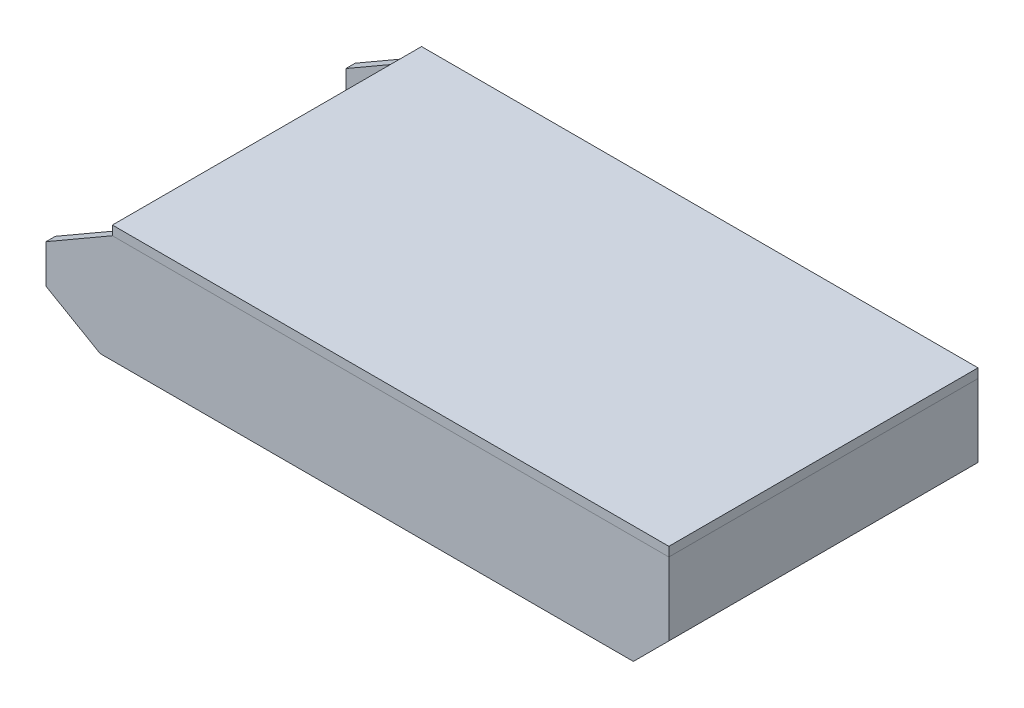
SolidWorks part; units mm, degrees
ref_plane "Front Plane" through (0, 0, 0) normal (0, 0, 1) x (1, 0, 0)
ref_plane "Top Plane" through (0, 0, 0) normal (0, 1, 0) x (1, 0, 0)
ref_plane "Right Plane" through (0, 0, 0) normal (1, 0, 0) x (0, 0, -1)
sketch "Sketch1" plane through (0, 0, 0) normal (0, 1, 0) x (1, 0, 0)
  line L0 (-180, 0) -> (180, 0) construction
  line L1 (-180, -100) -> (-180, 100) construction
  line L2 (-180, 100) -> (180, 100) construction
  line L3 (180, 100) -> (180, -100) construction
  line L4 (180, -100) -> (-180, -100) construction
  point P4 (0, 0)
  point P7 (-180, 0)
ref_plane "Back" through (180, 0, 0) normal (1, 0, 0) x (0, 0, -1)
ref_plane "Front" through (-180, 0, 0) normal (-1, 0, 0) x (0, 0, 1)
ref_plane "Left" through (0, 0, 100) normal (0, 0, 1) x (1, 0, 0)
ref_plane "Right" through (0, 0, -100) normal (0, 0, -1) x (-1, 0, 0)
sketch3d "3DSketch1"
  line L0 (-180, 0, 100) -> (-180, 300.6938, 100) construction
  line L1 (-180, 0, -100) -> (-180, 287.9975, -100) construction
  line L2 (180, 0, -100) -> (180, 282.9498, -100) construction
  line L3 (180, 0, 100) -> (180, 391.3038, 100) construction
  line L4 (-110, 0, -100) -> (-110, 0, 100) construction
  line L5 (-180, 0, -100) -> (180, 0, -100) construction
  line L6 (180, 0, 100) -> (-180, 0, 100) construction
  line L7 (157.0424, 0, 100) -> (157.0424, 0, -100) construction
  dimension "D1" = 110
  dimension "D2" = 157.0424
ref_plane "FrontMainBody" through (-55, -55, 0) normal (-0.7071, -0.7071, 0) x (0, 0, 1)
sketch "Left Panel(Main)" plane through (0, 0, 100) normal (0, 0, 1) x (1, 0, 0)
  line L0 (157.0424, 0) -> (-187.9576, 0)
  line L2 (-180, -200000) -> (-180, 200300.6938) construction
  line L3 (-180, 70) -> (180, 70)
  line L4 (180, -200000) -> (180, 200391.3038) construction
  line L5 (180, 70) -> (180, 22.9576)
  line L6 (180, 22.9576) -> (157.0424, 0)
  line L7 (-180, 70) -> (-222.9576, 45.1984)
  line L8 (-222.9576, 45.1984) -> (-222.9576, 20.2073)
  line L9 (-222.9576, 20.2073) -> (-187.9576, 0)
  line L10 (-180, 70) -> (-110, 0) construction
  dimension "D2" = 150
  dimension "D3" = 150
  dimension "D4" = 45
  dimension "D5" = 135
  dimension "D6" = 345
  dimension "D7" = 70
  dimension "D1" = 35
  dimension "D8" = 157.0424
sketch "Right Panel" plane through (0, 0, -100) normal (0, 0, -1) x (-1, 0, 0)
  line L0 (-180, 70) -> (180, 70)
  line L1 (180, 70) -> (222.9576, 45.1984)
  line L2 (222.9576, 45.1984) -> (222.9576, 20.2073)
  line L3 (222.9576, 20.2073) -> (187.9576, 0)
  line L4 (187.9576, 0) -> (-157.0424, 0)
  line L5 (-157.0424, 0) -> (-180, 22.9576)
  line L6 (-180, 22.9576) -> (-180, 70)
sketch3d "3DSketch4"
  line L0 (157.0424, 0, 100) -> (180, 22.9576, 100)
  line L1 (180, 22.9576, 100) -> (180, 70, 100)
  line L2 (180, 70, 100) -> (-180, 70, 100)
  line L3 (-180, 70, 100) -> (-222.9576, 45.1984, 100)
  line L4 (-222.9576, 45.1984, 100) -> (-222.9576, 20.2073, 100)
  line L5 (-222.9576, 20.2073, 100) -> (-187.9576, 0, 100)
  line L6 (-187.9576, 0, 100) -> (157.0424, 0, 100)
  line L7 (-187.9576, 0, -100) -> (157.0424, 0, -100)
  line L8 (-222.9576, 20.2073, -100) -> (-187.9576, 0, -100)
  line L9 (-222.9576, 45.1984, -100) -> (-222.9576, 20.2073, -100)
  line L10 (-180, 70, -100) -> (-222.9576, 45.1984, -100)
  line L11 (180, 70, -100) -> (-180, 70, -100)
  line L12 (180, 22.9576, -100) -> (180, 70, -100)
  line L13 (157.0424, 0, -100) -> (180, 22.9576, -100)
sketch "Sketch7" plane through (180, 0, 0) normal (1, 0, 0) x (0, 0, -1)
  line L0 (-94, 22.9576) -> (94, 22.9576)
  line L1 (-94, 22.9576) -> (-94, 70)
  line L2 (-94, 70) -> (94, 70)
  line L3 (94, 22.9576) -> (94, 70)
  dimension "D1" = 188
  dimension "D2" = 6
ref_plane "Plane2" through (78.5212, -78.5212, 0) normal (-0.7071, 0.7071, 0) x (0, 0, 1)
sketch "Sketch8" plane through (78.5212, -78.5212, 0) normal (-0.7071, 0.7071, 0) x (0, 0, 1)
  line L0 (-94, 143.5127) -> (-94, 111.0457)
  line L1 (-94, 111.0457) -> (94, 111.0457)
  line L2 (94, 111.0457) -> (94, 143.5127)
  line L3 (-94, 143.5127) -> (94, 143.5127)
  line L8 (100, 111.0457) -> (-100, 111.0457) construction
sketch "Sketch9" plane through (0, 0, 0) normal (0, 1, 0) x (1, 0, 0)
  line L0 (-110, -94) -> (151.0424, -94)
  line L1 (-110, 100) -> (-110, -100) construction
  line L3 (151.0424, -94) -> (151.0424, 94)
  line L4 (151.0424, 94) -> (-110, 94)
  line L5 (-110, 94) -> (-110, -94)
  line L6 (157.0424, -100) -> (-187.9576, -100) construction
  line L7 (-180, 100) -> (180, 100) construction
  dimension "D1" = 6
  dimension "D2" = 6
  dimension "D3" = 261.0424
extrude "Boss-Extrude2" add sketch "Right Panel" against normal blind 6
extrude "Boss-Extrude3" add sketch "Left Panel(Main)" against normal blind 6 separate body
sketch "Sketch12" plane through (0, 0, -94) normal (0, 0, 1) x (1, 0, 0)
  line L1 (-110, 8.4853) -> (-171.5147, 70)
  line L2 (-180, 70) -> (180, 70) construction
  line L3 (-171.5147, 70) -> (-180, 70)
  line L4 (-180, 70) -> (-110, 0)
  line L5 (-110, 0) -> (-110, 8.4853)
  line L6 (180, 70) -> (180, 22.9576) construction
  line L7 (-180, 70) -> (180, 70) construction
  dimension "D1" = 6
extrude "Boss-Extrude4" add sketch "Sketch12" along normal up to surface (188 mm away) separate body up to face at (-42.4044, 32.6233, 94)
sketch "Sketch13" plane through (0, 0, -94) normal (0, 0, 1) x (1, 0, 0)
  line L0 (180, 70) -> (174, 70)
  line L1 (-180, 70) -> (180, 70) construction
  line L2 (180, 70) -> (180, 22.9576)
  line L3 (180, 22.9576) -> (174, 22.9576)
  line L4 (174, 22.9576) -> (174, 70)
  dimension "D1" = 6
extrude "Boss-Extrude5" add sketch "Sketch13" along normal up to surface (188 mm away) separate body up to face at (-42.4044, 32.6233, 94)
sketch "Sketch14" plane through (0, 0, -94) normal (0, 0, 1) x (1, 0, 0)
  line L0 (180, 22.9576) -> (163.0424, 6)
  line L1 (163.0424, 6) -> (154.5571, 6)
  line L2 (154.5571, 6) -> (171.5147, 22.9576)
  line L3 (171.5147, 22.9576) -> (180, 22.9576)
  line L4 (157.0424, 0) -> (-187.9576, 0) construction
  line L5 (180, 22.9576) -> (157.0424, 0) construction
  point P3 (163.0424, 6)
  point P4 (173.8248, 22.9576)
  point P8 (0, 0)
  point P9 (172.1897, 22.9576)
  point P10 (151.0424, 0)
  point P14 (0, 0)
  dimension "D2" = 6
other "AlignGroup1"
sketch "Sketch15" plane through (0, 0, -94) normal (0, 0, 1) x (1, 0, 0)
  line L0 (-110, 0) -> (157.0424, 0)
  line L1 (-110, 0) -> (-110, 6)
  line L2 (-110, 0) -> (-110, 8.4853) construction
  line L3 (-110, 6) -> (163.0424, 6)
  line L4 (157.0424, 0) -> (163.0424, 6)
  line L5 (180, 70) -> (180, 22.9576) construction
  line L6 (-180, 70) -> (180, 70) construction
  dimension "D1" = 6
extrude "Boss-Extrude6" add sketch "Sketch15" along normal up to surface (188 mm away) up to face at (-42.4044, 32.6233, 94)
extrude "Boss-Extrude7" add sketch "Sketch14" along normal up to surface (188 mm away) up to face at (21.9213, 30.5738, 94)
sketch "Sketch16" plane through (0, 70, 0) normal (0, 1, 0) x (1, 0, 0)
  line L0 (-180, 100) -> (180, 100)
  line L1 (180, 100) -> (180, -100)
  line L2 (180, -100) -> (-180, -100)
  line L3 (-180, -100) -> (-180, 100)
extrude "Boss-Extrude8" add sketch "Sketch16" along normal blind 6 separate body
equation "\"FrontAngle\"= 150deg"
equation "\"D2@Left Panel(Main)\" = \"FrontAngle\""
equation "\"D3@Left Panel(Main)\" = \"FrontAngle\""
